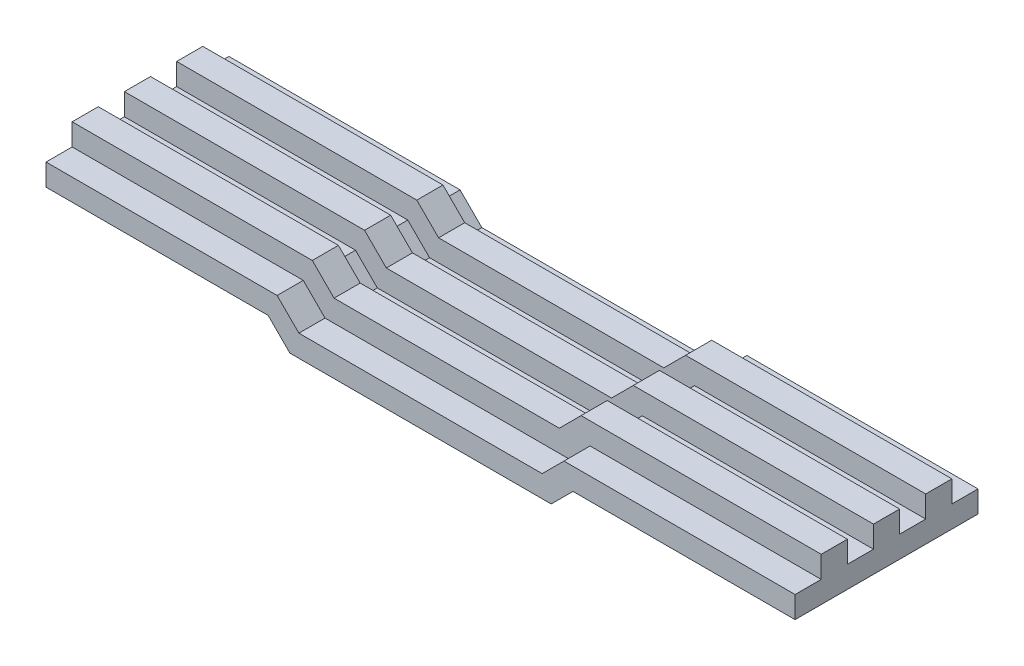
SolidWorks part; units mm, degrees
ref_plane "Front Plane" through (0, 0, 0) normal (0, 0, 1) x (1, 0, 0)
ref_plane "Top Plane" through (0, 0, 0) normal (0, 1, 0) x (1, 0, 0)
ref_plane "Right Plane" through (0, 0, 0) normal (1, 0, 0) x (0, 0, -1)
sketch "Sketch1" plane through (0, 0, 0) normal (1, 0, 0) x (0, 0, -1)
  line L0 (0, 12.5054) -> (0, -7.7638) construction
  line L1 (10.5, 0) -> (-10.5, 0)
  line L2 (-10.5, 0) -> (-10.5, 2.5)
  line L3 (-10.5, 2.5) -> (-7.5, 2.5)
  line L4 (-7.5, 2.5) -> (-7.5, 5)
  line L5 (-7.5, 5) -> (-4.5, 5)
  line L6 (-4.5, 5) -> (-4.5, 2.5)
  line L7 (-4.5, 2.5) -> (-1.5, 2.5)
  line L8 (-1.5, 2.5) -> (-1.5, 5)
  line L9 (-1.5, 5) -> (1.5, 5)
  line L10 (1.5, 2.5) -> (1.5, 5)
  line L11 (4.5, 2.5) -> (1.5, 2.5)
  line L12 (4.5, 5) -> (4.5, 2.5)
  line L13 (7.5, 5) -> (4.5, 5)
  line L14 (7.5, 2.5) -> (7.5, 5)
  line L15 (10.5, 2.5) -> (7.5, 2.5)
  line L16 (10.5, 0) -> (10.5, 2.5)
  point P14 (0, 5)
  point P21 (0, 0)
  dimension "D1" = 15
  dimension "D2" = 21
  dimension "D3" = 2.5
  dimension "D4" = 2.5
sketch "Sketch2" plane through (0, 0, 0) normal (0, 0, 1) x (1, 0, 0)
  line L0 (0, 47.8818) -> (0, -32.5095) construction
  line L1 (15, 0) -> (-15, 0)
  line L2 (-15, 0) -> (-17.5, 2.5)
  line L3 (-17.5, 2.5) -> (-43, 2.5)
  line L4 (17.5, 2.5) -> (43, 2.5)
  line L5 (15, 0) -> (17.5, 2.5)
  point P10 (0, 0)
  dimension "D1" = 86
  dimension "D2" = 30
  dimension "D3" = 2.5
  dimension "D4" = 45
sweep "Sweep1" add profiles "Sketch1" path "Sketch2"
